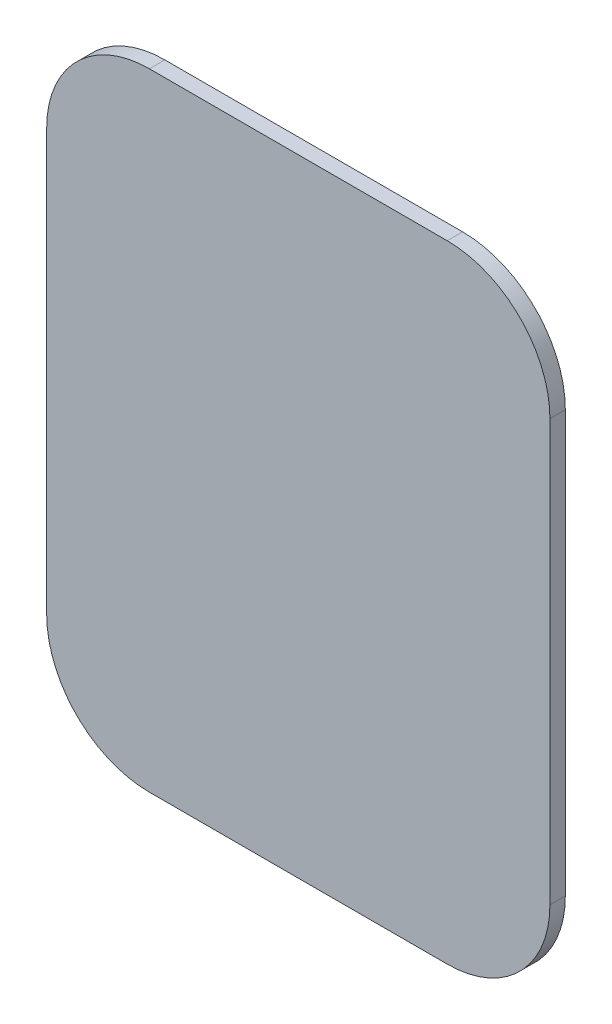
SolidWorks part; units mm, degrees
ref_plane "前视基准面" through (0, 0, 0) normal (0, 0, 1) x (1, 0, 0)
ref_plane "上视基准面" through (0, 0, 0) normal (0, 1, 0) x (1, 0, 0)
ref_plane "右视基准面" through (0, 0, 0) normal (1, 0, 0) x (0, 0, -1)
sketch "草图1" plane through (0, 0, 0) normal (0, 0, 1) x (1, 0, 0)
  line L1 (-49, 61) -> (49, 61)
  line L2 (-49, 61) -> (-49, -61)
  line L3 (-49, -61) -> (49, -61)
  line L4 (49, 61) -> (49, -61)
  line L5 (-49, 61) -> (49, -61) construction
  line L6 (-49, -61) -> (49, 61) construction
  point P0 (0, 0)
  dimension "D1" = 98
  dimension "D2" = 122
extrude "凸台-拉伸1" add sketch "草图1" along normal blind 3
fillet "圆角1" radius 20 4 edges at (-49, 61, 1.5) (-49, -61, 1.5) (49, -61, 1.5) (49, 61, 1.5)
